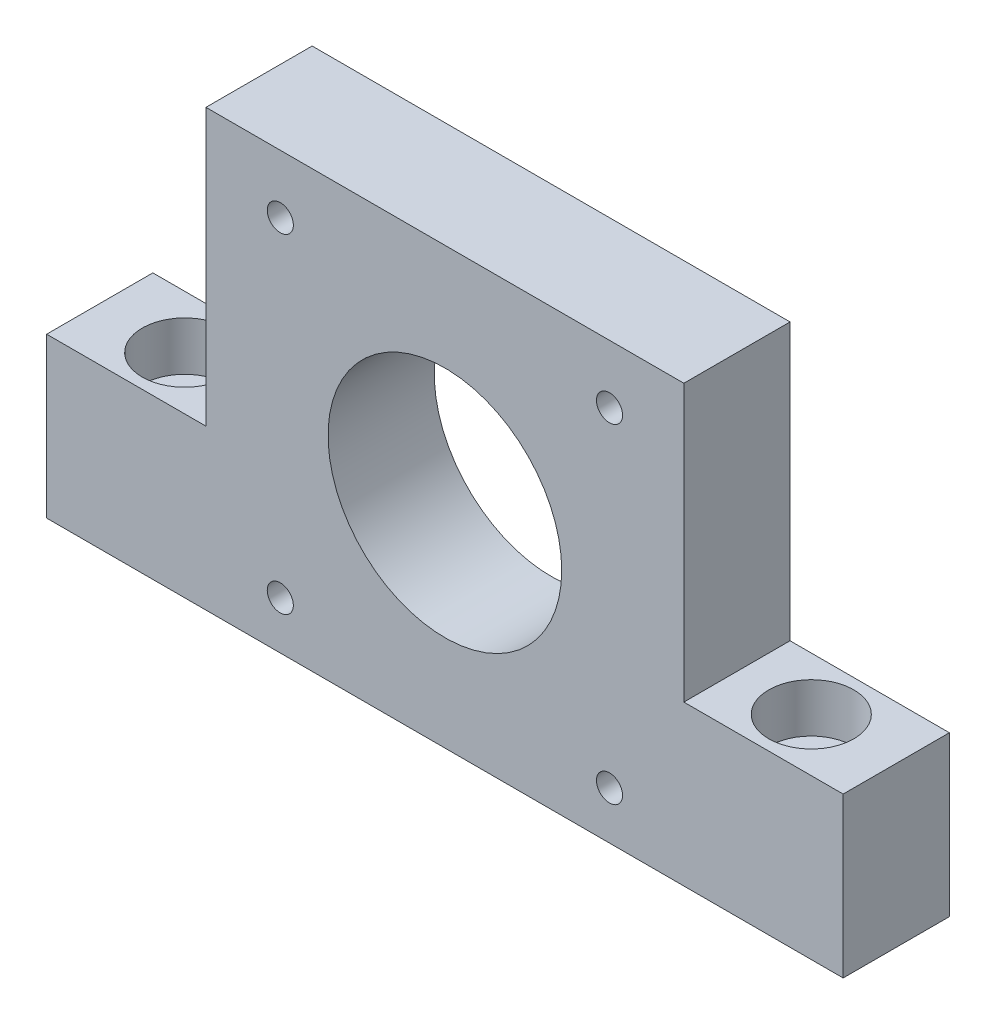
SolidWorks part; units mm, degrees
ref_plane "前视基准面" through (0, 0, 0) normal (0, 0, 1) x (1, 0, 0)
ref_plane "上视基准面" through (0, 0, 0) normal (0, 1, 0) x (1, 0, 0)
ref_plane "右视基准面" through (0, 0, 0) normal (1, 0, 0) x (0, 0, -1)
other "Configuration Table"
sketch "草图1" plane through (0, 0, 0) normal (0, 0, 1) x (1, 0, 0)
  line L0 (0, 0) -> (75, 0)
  line L1 (75, 0) -> (75, 15)
  line L2 (75, 15) -> (60, 15)
  line L3 (60, 15) -> (60, 41)
  line L4 (60, 41) -> (15, 41)
  line L5 (15, 41) -> (15, 15)
  line L6 (15, 15) -> (0, 15)
  line L7 (0, 15) -> (0, 0)
  line L8 (37.5, 0) -> (37.5, 68.4466) construction
  dimension "D1" = 45
  dimension "D2" = 26
  dimension "D3" = 15
  dimension "D4" = 15
extrude "凸台-拉伸1" add sketch "草图1" along normal blind 10
sketch "草图2" plane through (0, 0, 10) normal (0, 0, 1) x (1, 0, 0)
  line L0 (37.5, 0) -> (37.5, 51.8003) construction
  line L1 (0, 0) -> (75, 0) construction
  circle A0 centre (37.5, 20) radius 11
  dimension "D1" = 22
  dimension "D2" = 20
extrude "切除-拉伸1" cut sketch "草图2" against normal through all
sketch "草图3" plane through (0, 0, 0) normal (0, 0, -1) x (-1, 0, 0)
  line L0 (-37.5, 20) -> (-37.5, -10.9068) construction
  line L1 (-37.5, 20) -> (-19.8848, 20) construction
  circle A0 centre (-22, 4.5) radius 1.2295
  circle A1 centre (-37.5, 20) radius 21.9203 construction
  circle A2 centre (-53, 4.5) radius 1.2295
  circle A3 centre (-53, 35.5) radius 1.2295
  circle A4 centre (-22, 35.5) radius 1.2295
  point P12 (0, 0)
  point P13 (0, 0)
  point P14 (-47.5, 20)
  point P15 (-37.5, 20)
  point P17 (-53, 35.5)
  dimension "D1" = 2.459
sketch "草图4" plane through (0, 15, 0) normal (0, 1, 0) x (1, 0, 0)
  line L0 (0, -5) -> (76.1413, -5) construction
  line L1 (0, -10) -> (0, 0) construction
  line L2 (15, -10) -> (15, 0) construction
  line L3 (60, -10) -> (60, 0) construction
  circle A0 centre (8, -5) radius 2
  circle A1 centre (67, -5) radius 2
  dimension "D3" = 4
  dimension "D4" = 4
  dimension "D1" = 7
  dimension "D2" = 7
hole_wizard "M4 六角圆柱头螺钉的柱形沉头孔1" positions "3D草图1" profile "草图5" counterbore size "M4" standard "GB" end condition through all
sketch3d "3D草图1"
  point P0 (8, 15, 5)
  point P3 (67, 15, 5)
sketch "草图5" plane through (8, 15, 5) normal (1, 0, 0) x (0, 0, 1)
  line L0 (0, 0) -> (0, 15)
  line L1 (0, 15) -> (2.25, 15)
  line L3 (2.25, 15) -> (2.25, 4.6)
  line L4 (2.25, 4.6) -> (4, 4.6)
  line L5 (4, 4.6) -> (4, 0)
  line L7 (4, 0) -> (0, 0)
  line L11 (0, -6.35) -> (0, 107.95) construction
  dimension "通孔孔直径" = 4.5
  dimension "通孔孔深度" = 15
  dimension "柱形沉头孔直径" = 8
  dimension "柱形沉头孔深度" = 4.6
extrude "切除-拉伸2" cut sketch "草图3" against normal through all
